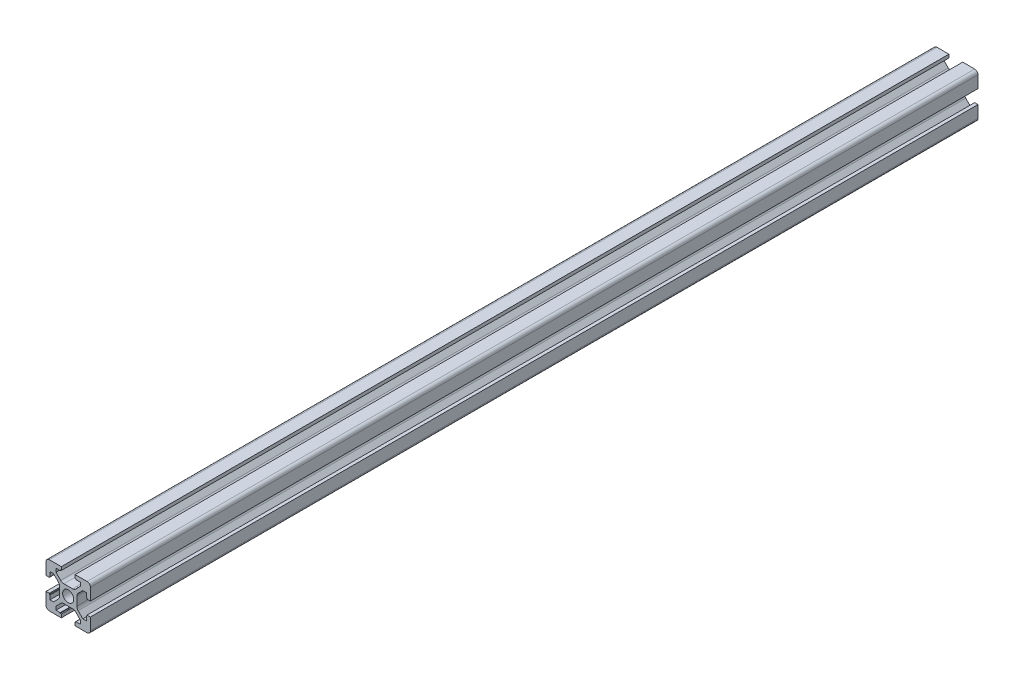
SolidWorks part; units mm, degrees
material "6063-T5"
ref_plane "Front Plane" through (0, 0, 0) normal (0, 0, 1) x (1, 0, 0)
ref_plane "Top Plane" through (0, 0, 0) normal (0, 1, 0) x (1, 0, 0)
ref_plane "Right Plane" through (0, 0, 0) normal (1, 0, 0) x (0, 0, -1)
sketch "Sketch1" plane through (0, 0, 0) normal (0, 0, 1) x (1, 0, 0)
  line L0 (0, 0) -> (0, 15) construction
  line L1 (-10, 10) -> (0, 10) construction
  line L2 (-10, 10) -> (-10, 0) construction
  line L3 (1.9716, 3.9) -> (-1.9716, 3.9)
  line L4 (-3.3858, 4.4858) -> (-5.5, 6.6)
  line L5 (0, 0) -> (-15, 0) construction
  line L6 (-5.5, 6.6) -> (-5.5, 8.2)
  line L7 (-5.5, 8.2) -> (-3.6, 8.2)
  line L8 (-3.6, 8.2) -> (-3.6, 8.5)
  line L9 (-3.6, 8.5) -> (-3.1, 8.5)
  line L10 (-3.1, 8.5) -> (-3.1, 10)
  line L11 (-3.1, 10) -> (-8.5, 10)
  line L12 (-10, 8.5) -> (-10, 3.1)
  line L13 (-10, 3.1) -> (-8.5, 3.1)
  line L14 (-8.5, 3.1) -> (-8.5, 3.6)
  line L15 (-8.5, 3.6) -> (-8.2, 3.6)
  line L16 (-8.2, 3.6) -> (-8.2, 5.5)
  line L17 (-8.2, 5.5) -> (-6.6, 5.5)
  line L18 (-6.6, 5.5) -> (-4.4858, 3.3858)
  line L19 (-3.9, 1.9716) -> (-3.9, -1.9716)
  line L20 (3.9, 1.9716) -> (3.9, -1.9716)
  line L21 (6.6, 5.5) -> (4.4858, 3.3858)
  line L22 (8.2, 5.5) -> (6.6, 5.5)
  line L23 (8.2, 3.6) -> (8.2, 5.5)
  line L24 (8.5, 3.6) -> (8.2, 3.6)
  line L25 (8.5, 3.1) -> (8.5, 3.6)
  line L26 (10, 3.1) -> (8.5, 3.1)
  line L27 (10, 8.5) -> (10, 3.1)
  line L28 (3.1, 10) -> (8.5, 10)
  line L29 (3.1, 8.5) -> (3.1, 10)
  line L30 (3.6, 8.5) -> (3.1, 8.5)
  line L31 (3.6, 8.2) -> (3.6, 8.5)
  line L32 (5.5, 8.2) -> (3.6, 8.2)
  line L33 (5.5, 6.6) -> (5.5, 8.2)
  line L34 (3.3858, 4.4858) -> (5.5, 6.6)
  line L35 (6.6, -5.5) -> (4.4858, -3.3858)
  line L36 (8.2, -5.5) -> (6.6, -5.5)
  line L37 (8.2, -3.6) -> (8.2, -5.5)
  line L38 (8.5, -3.6) -> (8.2, -3.6)
  line L39 (8.5, -3.1) -> (8.5, -3.6)
  line L40 (10, -3.1) -> (8.5, -3.1)
  line L41 (10, -8.5) -> (10, -3.1)
  line L42 (3.1, -10) -> (8.5, -10)
  line L43 (3.1, -8.5) -> (3.1, -10)
  line L44 (3.6, -8.5) -> (3.1, -8.5)
  line L45 (3.6, -8.2) -> (3.6, -8.5)
  line L46 (5.5, -8.2) -> (3.6, -8.2)
  line L47 (5.5, -6.6) -> (5.5, -8.2)
  line L48 (3.3858, -4.4858) -> (5.5, -6.6)
  line L49 (1.9716, -3.9) -> (-1.9716, -3.9)
  line L50 (-3.3858, -4.4858) -> (-5.5, -6.6)
  line L51 (-5.5, -6.6) -> (-5.5, -8.2)
  line L52 (-5.5, -8.2) -> (-3.6, -8.2)
  line L53 (-3.6, -8.2) -> (-3.6, -8.5)
  line L54 (-3.6, -8.5) -> (-3.1, -8.5)
  line L55 (-3.1, -8.5) -> (-3.1, -10)
  line L56 (-3.1, -10) -> (-8.5, -10)
  line L57 (-10, -8.5) -> (-10, -3.1)
  line L58 (-10, -3.1) -> (-8.5, -3.1)
  line L59 (-8.5, -3.1) -> (-8.5, -3.6)
  line L60 (-8.5, -3.6) -> (-8.2, -3.6)
  line L61 (-8.2, -3.6) -> (-8.2, -5.5)
  line L62 (-8.2, -5.5) -> (-6.6, -5.5)
  line L63 (-6.6, -5.5) -> (-4.4858, -3.3858)
  circle A0 centre (0, 0) radius 2.5
  arc A1 (-10, -8.5) -> (-8.5, -10) centre (-8.5, -8.5) ccw
  arc A2 (8.5, -10) -> (10, -8.5) centre (8.5, -8.5) ccw
  arc A3 (10, 8.5) -> (8.5, 10) centre (8.5, 8.5) ccw
  arc A4 (-8.5, 10) -> (-10, 8.5) centre (-8.5, 8.5) ccw
  arc A5 (-3.3858, -4.4858) -> (-1.9716, -3.9) centre (-1.9716, -5.9) cw
  arc A6 (1.9716, -3.9) -> (3.3858, -4.4858) centre (1.9716, -5.9) cw
  arc A7 (4.4858, -3.3858) -> (3.9, -1.9716) centre (5.9, -1.9716) cw
  arc A8 (3.9, 1.9716) -> (4.4858, 3.3858) centre (5.9, 1.9716) cw
  arc A9 (1.9716, 3.9) -> (3.3858, 4.4858) centre (1.9716, 5.9) ccw
  arc A10 (-1.9716, 3.9) -> (-3.3858, 4.4858) centre (-1.9716, 5.9) cw
  arc A11 (-4.4858, 3.3858) -> (-3.9, 1.9716) centre (-5.9, 1.9716) cw
  arc A12 (-3.9, -1.9716) -> (-4.4858, -3.3858) centre (-5.9, -1.9716) cw
  point P40 (0, 3.9)
  point P41 (3.9, 0)
  point P70 (-3.9, 0)
  point P72 (-10, -10)
  point P75 (10, -10)
  point P78 (10, 10)
  point P84 (-2.8, -3.9)
  point P87 (2.8, -3.9)
  point P90 (3.9, -2.8)
  point P93 (3.9, 2.8)
  point P96 (2.8, 3.9)
  point P99 (-2.8, 3.9)
  point P102 (-3.9, 2.8)
  point P105 (-3.9, -2.8)
  dimension "D3" = 5
  dimension "D14" = 1.5
  dimension "D15" = 2
  dimension "D1" = 10
  dimension "D2" = 10
  dimension "D4" = 15
  dimension "D5" = 5.5
  dimension "D6" = 3.4
  dimension "D7" = 6.1
  dimension "D8" = 6.1
  dimension "D9" = 3.1
  dimension "D10" = 3.6
  dimension "D11" = 1.5556
  dimension "D12" = 1.8
  dimension "D13" = 1.5
extrude "Boss-Extrude1" add sketch "Sketch1" along normal blind 400
